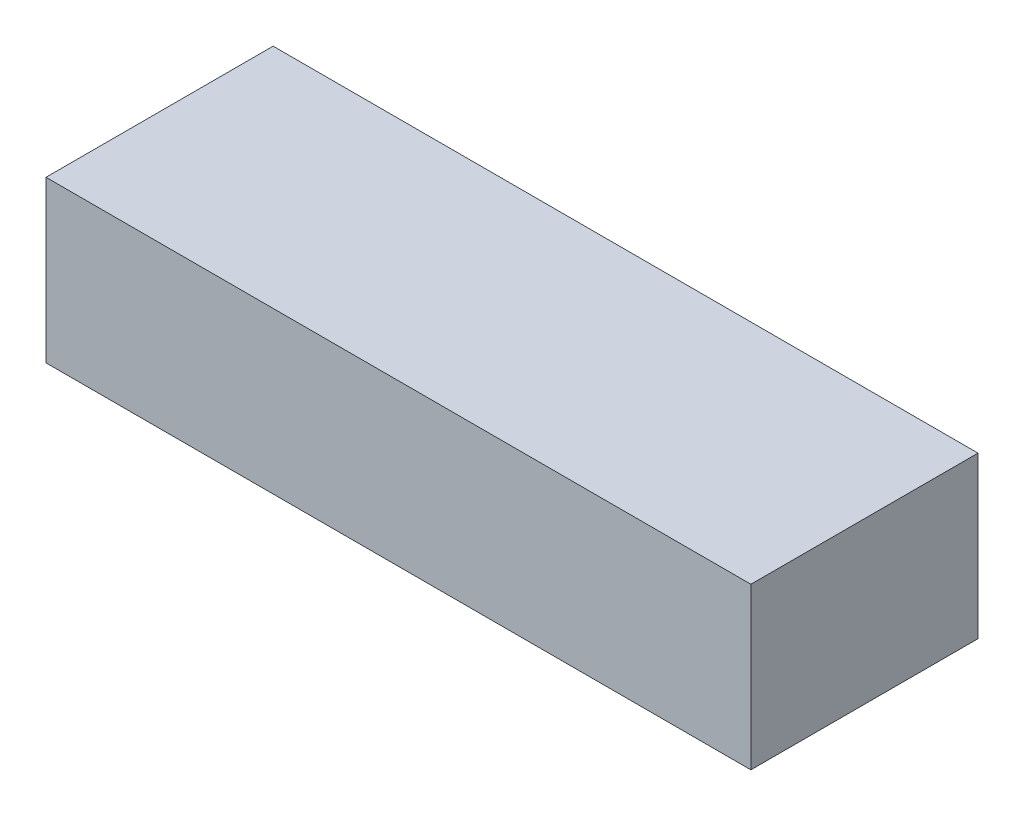
SolidWorks part; units mm, degrees
ref_plane "Front Plane" through (0, 0, 0) normal (0, 0, 1) x (1, 0, 0)
ref_plane "Top Plane" through (0, 0, 0) normal (0, 1, 0) x (1, 0, 0)
ref_plane "Right Plane" through (0, 0, 0) normal (1, 0, 0) x (0, 0, -1)
sketch "Sketch1" plane through (0, 0, 0) normal (0, 1, 0) x (1, 0, 0)
  line L1 (-67.97, 21.9) -> (67.97, 21.9)
  line L2 (-67.97, 21.9) -> (-67.97, -21.9)
  line L3 (-67.97, -21.9) -> (67.97, -21.9)
  line L4 (67.97, 21.9) -> (67.97, -21.9)
  line L5 (-67.97, 21.9) -> (67.97, -21.9) construction
  line L6 (-67.97, -21.9) -> (67.97, 21.9) construction
  point P0 (0, 0)
  dimension "D1" = 135.94
  dimension "D2" = 43.8
extrude "Boss-Extrude1" add sketch "Sketch1" along normal blind 31
